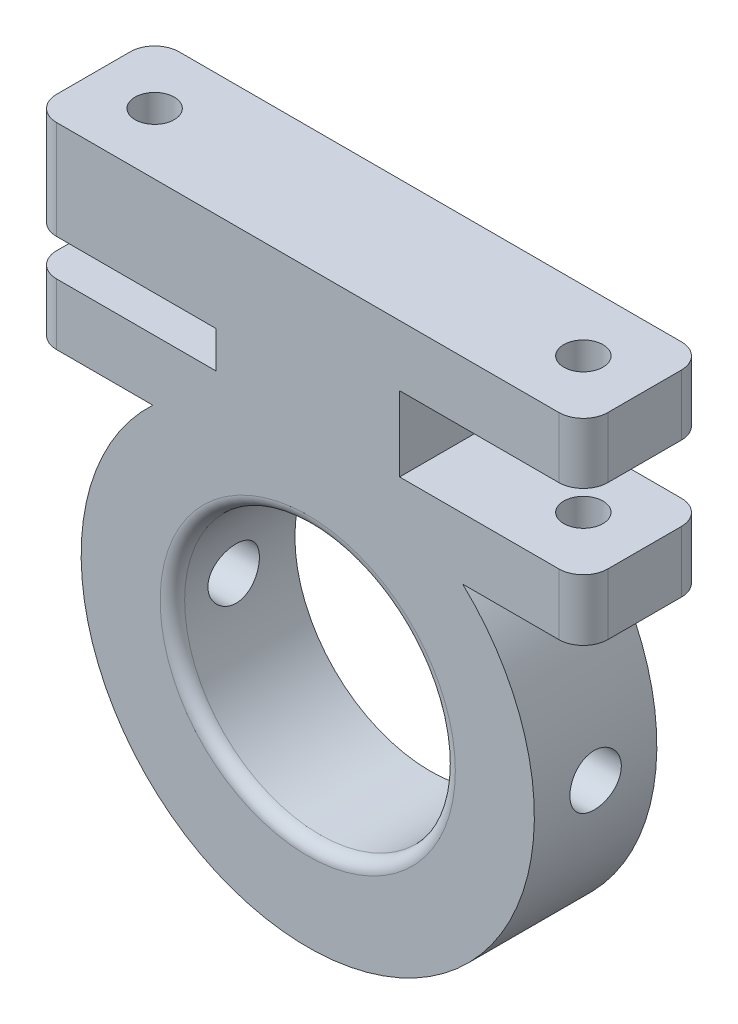
SolidWorks part; units mm, degrees
ref_plane "Alzado" through (0, 0, 0) normal (0, 0, 1) x (1, 0, 0)
ref_plane "Planta" through (0, 0, 0) normal (0, 1, 0) x (1, 0, 0)
ref_plane "Vista lateral" through (0, 0, 0) normal (1, 0, 0) x (0, 0, -1)
sketch "Croquis1" plane through (0, 0, 0) normal (0, 0, 1) x (1, 0, 0)
  line L0 (-22.5, 18.5) -> (22.5, 18.5)
  line L1 (-22.5, 18.5) -> (-22.5, 13.5)
  line L2 (-22.5, 13.5) -> (-12.6491, 13.5)
  line L3 (0, 0) -> (0, 31.049) construction
  line L4 (-7.5, 18.5) -> (-7.5, 24.6)
  line L5 (-7.5, 24.6) -> (7.5, 24.6)
  line L6 (7.5, 24.6) -> (7.5, 18.5)
  line L7 (-22.5, 24.5583) -> (-22.5, 21.5)
  line L8 (-22.5, 24.5583) -> (-22.5, 29.5583)
  line L9 (-22.5, 29.5583) -> (22.5, 29.5583)
  line L10 (22.5, 29.5583) -> (22.5, 24.6)
  line L11 (22.5, 24.6) -> (7.5, 24.6)
  line L12 (22.5, 18.5) -> (22.5, 13.5)
  line L13 (22.5, 13.5) -> (12.6491, 13.5)
  line L14 (-22.5, 21.5) -> (-7.5, 21.5)
  circle A0 centre (0, 0) radius 18.5
  circle A1 centre (0, 0) radius 11.05
  point P7 (0, 18.5)
  point P15 (0, 24.6)
  dimension "D1" = 22.1
  dimension "D2" = 37
  dimension "D3" = 45
  dimension "D4" = 5
  dimension "D5" = 6.1
  dimension "D6" = 5
  dimension "D7" = 15
  dimension "D8" = 3
extrude "Saliente-Extruir2" add sketch "Croquis1" along normal mid plane 10
sketch "Croquis2" plane through (0, 29.5583, 0) normal (0, 1, 0) x (1, 0, 0)
  line L0 (-17.5, 0) -> (17.5, 0)
  circle A0 centre (-17.5, 0) radius 1.6
  circle A1 centre (17.5, 0) radius 1.6
  point P4 (0, 0)
  dimension "D1" = 3.2
  dimension "D2" = 3.2
  dimension "D3" = 35
extrude "Cortar-Extruir1" cut sketch "Croquis2" against normal blind 18
fillet "Redondeo1" radius 1 1 edges at (11.05, 0, 5)
sketch "Croquis3" plane through (0, 0, 0) normal (1, 0, 0) x (0, 0, -1)
  circle A0 centre (0, 0) radius 2.1
  dimension "D1" = 4.2
extrude "Cortar-Extruir2" cut sketch "Croquis3" against normal through all both and the other way through all
fillet "Redondeo2" radius 2 8 edges at (-22.5, 16, -5) (-22.5, 16, 5) (22.5, 16, -5) (22.5, 16, 5) (22.5, 27.0791, -5) (22.5, 27.0791, 5) (-22.5, 25.5291, -5) (-22.5, 25.5291, 5)
